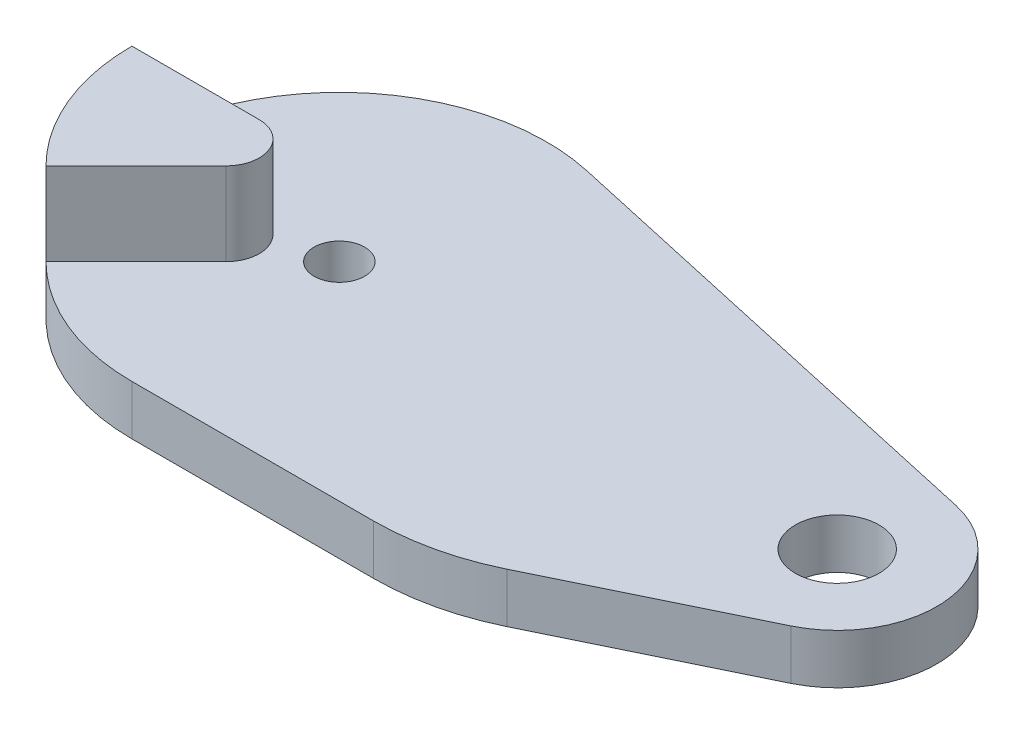
SolidWorks part; units mm, degrees
material "ABS"
ref_plane "前视基准面" through (0, 0, 0) normal (0, 0, 1) x (1, 0, 0)
ref_plane "上视基准面" through (0, 0, 0) normal (0, 1, 0) x (1, 0, 0)
ref_plane "右视基准面" through (0, 0, 0) normal (1, 0, 0) x (0, 0, -1)
other "Configuration Table"
sketch "草图1" plane through (0, 0, 0) normal (0, 1, 0) x (1, 0, 0)
  circle A0 centre (0, 0) radius 3.05
  circle A1 centre (0, 0) radius 12.5
  dimension "D1" = 6.1
  dimension "D2" = 25
extrude "凸台-拉伸1" add sketch "草图1" along normal blind 8 contours A0 | A1
sketch "草图2" plane through (0, 0, 0) normal (0, 0, 1) x (1, 0, 0)
  line L0 (12.5, 0) -> (12.5, 8) construction
  line L1 (-12.5, 8) -> (-12.5, 0) construction
  line L2 (-12.5, 0) -> (12.5, 0) construction
  line L3 (12.5, 8) -> (-12.5, 8) construction
  line L4 (12.5, 0) -> (12.5, 8) construction
  line L5 (-12.5, 8) -> (-12.5, 0) construction
  line L6 (-12.5, 0) -> (12.5, 0) construction
  line L7 (12.5, 8) -> (-12.5, 8) construction
  line L8 (-5.2696, 1.7) -> (6.282, 1.7) construction
  circle A0 centre (0, 3.3) radius 1.6
  dimension "D1" = 3.2
  dimension "D2" = 3.3
extrude "切除-拉伸4" cut sketch "草图2" against normal mid plane 25
sketch "草图3" plane through (0, 8, 0) normal (0, 1, 0) x (1, 0, 0)
  line L2 (0, 0) -> (60, 0) construction
  line L5 (5.4167, 24.4061) -> (62.6, 11.7149)
  line L6 (0, -25) -> (36, -25)
  line L7 (36, -25) -> (65.2435, -10.7938)
  circle A0 centre (0, 0) radius 12.5 construction
  circle A1 centre (0, 0) radius 12.5 construction
  circle A2 centre (60, 0) radius 5.05
  arc A5 (65.2435, -10.7938) -> (62.6, 11.7149) centre (60, 0) ccw
  arc A6 (0, -25) -> (5.4167, 24.4061) centre (0, 0) cw
  dimension "D1" = 10.1
  dimension "D3" = 36
  dimension "D4" = 25
  dimension "D6" = 12
  dimension "D2" = 60
extrude "凸台-拉伸2" add sketch "草图3" along normal blind 6
sketch "草图4" plane through (0, 8, 0) normal (0, -1, 0) x (1, 0, 0)
  line L2 (5.4167, -24.4061) -> (62.6, -11.7149)
  line L3 (65.2435, 10.7938) -> (36, 25)
  line L6 (5.4167, -24.4061) -> (62.6, -11.7149) construction
  line L10 (65.2435, 10.7938) -> (36, 25) construction
  line L11 (36, 25) -> (0, 25)
  line L12 (36, 25) -> (0, 25) construction
  circle A0 centre (0, 0) radius 12.5 construction
  circle A1 centre (0, 0) radius 12.5 construction
  circle A2 centre (0, 0) radius 18
  arc A4 (0, 25) -> (5.4167, -24.4061) centre (0, 0) ccw
  arc A5 (62.6, -11.7149) -> (65.2435, 10.7938) centre (60, 0) ccw
  arc A6 (0, 25) -> (5.4167, -24.4061) centre (0, 0) ccw construction
  arc A7 (62.6, -11.7149) -> (65.2435, 10.7938) centre (60, 0) ccw construction
  dimension "D2" = 36
  dimension "D1" = 0
extrude "凸台-拉伸3" add sketch "草图4" along normal blind 2
fillet "圆角2" radius 30 1 edges at (36, 11, 25)
fillet "圆角1" radius 1 1 edges at (0, 6, -18)
sketch "草图5" plane through (0, 14, 0) normal (0, 1, 0) x (1, 0, 0)
  line L0 (0, 0) -> (-25, 0)
  line L1 (0, 0) -> (-17.6777, -17.6777)
  line L2 (-29.9138, 0) -> (127.3949, 0) construction
  line L3 (0, -25) -> (29.0988, -25)
  line L4 (42.2075, -21.9844) -> (65.2435, -10.7938)
  line L5 (62.6, 11.7149) -> (5.4167, 24.4061)
  line L6 (0, -25) -> (29.0988, -25) construction
  line L7 (42.2075, -21.9844) -> (65.2435, -10.7938) construction
  line L8 (62.6, 11.7149) -> (5.4167, 24.4061) construction
  arc A0 (-17.6777, -17.6777) -> (-25, 0) centre (0, 0) cw
  arc A3 (29.0988, -25) -> (42.2075, -21.9844) centre (29.0988, 5) ccw
  arc A4 (65.2435, -10.7938) -> (62.6, 11.7149) centre (60, 0) ccw
  arc A5 (5.4167, 24.4061) -> (0, -25) centre (0, 0) ccw
  arc A6 (29.0988, -25) -> (42.2075, -21.9844) centre (29.0988, 5) ccw construction
  arc A7 (65.2435, -10.7938) -> (62.6, 11.7149) centre (60, 0) ccw construction
  arc A8 (5.4167, 24.4061) -> (0, -25) centre (0, 0) ccw construction
  dimension "D2" = 45
  dimension "D3" = 135
  dimension "D1" = 0
extrude "凸台-拉伸4" add sketch "草图5" along normal blind 10
fillet "圆角3" radius 4 1 edges at (0, 19, 0)
sketch "草图6" plane through (0, 0, 0) normal (0, -1, 0) x (1, 0, 0)
  circle A0 centre (0, 0) radius 3.05 construction
  circle A1 centre (0, 0) radius 3.05
extrude "切除-拉伸5" cut sketch "草图6" against normal up to surface (14 mm away) up to face at (14.927, 14, 6.4486)
sketch "草图8" plane through (0, 0, 0) normal (0, -1, 0) x (1, 0, 0)
  line L0 (0, 0) -> (0, 11) construction
  line L1 (-5.9372, 11) -> (5.9372, 11)
  line L2 (-5.9372, -11) -> (5.9372, -11)
  arc A0 (5.9372, 11) -> (-5.9372, 11) centre (0, 0) ccw
  circle A1 centre (0, 0) radius 12.5
  circle A2 centre (0, 0) radius 12.5 construction
  arc A3 (5.9372, -11) -> (-5.9372, -11) centre (0, 0) cw
  circle M4 centre (0, 0) radius 12.5
  dimension "D2" = 11
  dimension "D1" = 0
extrude "切除-拉伸6" cut sketch "草图8" against normal up to surface (6 mm away) contours L1 M4 | L2 M4 up to face at (0, 6, -17)
